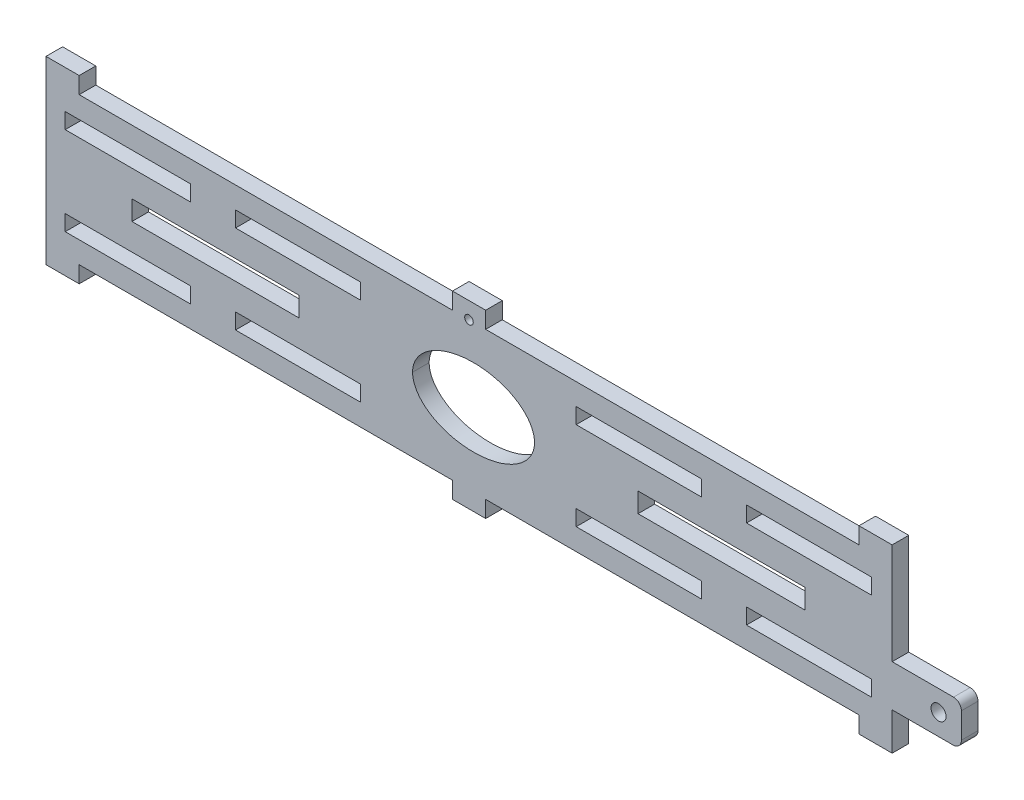
SolidWorks part; units mm, degrees
ref_plane "前视基准面" through (0, 0, 0) normal (0, 0, 1) x (1, 0, 0)
ref_plane "上视基准面" through (0, 0, 0) normal (0, 1, 0) x (1, 0, 0)
ref_plane "右视基准面" through (0, 0, 0) normal (1, 0, 0) x (0, 0, -1)
sketch "草图1" plane through (0, 0, 0) normal (0, 0, 1) x (1, 0, 0)
  line L0 (17.1779, 1.1844) -> (17.1779, -1.1844)
  line L1 (37.2925, 1.1844) -> (17.1779, 1.1844)
  line L2 (37.2925, -1.1844) -> (37.2925, 1.1844)
  line L3 (17.1779, -1.1844) -> (37.2925, -1.1844)
  line L4 (45.3383, -4.3798) -> (30.2524, -4.3798)
  line L5 (45.3383, -6.2719) -> (45.3383, -4.3798)
  line L6 (30.2524, -6.2719) -> (45.3383, -6.2719)
  line L7 (30.2524, -4.3798) -> (30.2524, -6.2719)
  line L8 (-50.1906, 8.875) -> (-50.1906, 10.875)
  line L9 (-50.1906, 10.875) -> (-54.1906, 10.875)
  line L10 (-54.1906, 10.875) -> (-54.1906, -10.875)
  line L11 (-1.1906, 10.875) -> (-5.1906, 10.875)
  line L12 (-50.1906, -10.875) -> (-50.1906, -8.875)
  line L13 (-50.1906, -8.875) -> (-5.1906, -8.875)
  line L14 (-5.1906, -8.875) -> (-5.1906, -10.875)
  line L15 (-1.1906, -10.875) -> (-5.1906, -10.875)
  line L16 (-1.1906, -10.875) -> (-1.1906, -8.875)
  line L17 (-1.1906, -8.875) -> (43.8094, -8.875)
  line L18 (43.8094, -8.875) -> (43.8094, -10.875)
  line L19 (-50.1906, -10.875) -> (-54.1906, -10.875)
  line L20 (47.8094, -10.875) -> (47.8094, -6.3479)
  line L21 (47.8094, -6.3479) -> (55.152, -6.3479)
  line L22 (56.1578, -5.3421) -> (56.1578, -2.2702)
  line L23 (55.2068, -1.3192) -> (47.8094, -1.3192)
  line L24 (47.8094, -1.3192) -> (47.8094, 10.875)
  line L25 (-43.8297, 0) -> (37.2925, 0) construction
  line L26 (43.8094, 10.875) -> (43.8094, 8.875)
  line L27 (43.8094, 8.875) -> (-1.1906, 8.875)
  line L28 (-1.1906, 8.875) -> (-1.1906, 10.875)
  line L29 (-43.8297, 0) -> (-54.1906, 0) construction
  line L30 (-5.1906, 10.875) -> (-5.1906, 8.875)
  line L31 (-5.1906, 8.875) -> (-50.1906, 8.875)
  line L32 (24.8063, -4.3798) -> (9.7204, -4.3798)
  line L33 (24.8063, -6.2719) -> (24.8063, -4.3798)
  line L34 (9.7204, -6.2719) -> (24.8063, -6.2719)
  line L35 (9.7204, -4.3798) -> (9.7204, -6.2719)
  line L36 (-16.2576, -4.3798) -> (-31.3436, -4.3798)
  line L37 (-16.2576, -6.2719) -> (-16.2576, -4.3798)
  line L38 (-31.3436, -6.2719) -> (-16.2576, -6.2719)
  line L39 (-31.3436, -4.3798) -> (-31.3436, -6.2719)
  line L40 (-36.7896, -4.3798) -> (-51.8755, -4.3798)
  line L41 (-36.7896, -6.2719) -> (-36.7896, -4.3798)
  line L42 (-51.8755, -6.2719) -> (-36.7896, -6.2719)
  line L43 (-51.8755, -4.3798) -> (-51.8755, -6.2719)
  line L44 (-43.8297, -1.1844) -> (-23.7151, -1.1844)
  line L45 (-43.8297, 1.1844) -> (-43.8297, -1.1844)
  line L46 (-23.7151, 1.1844) -> (-43.8297, 1.1844)
  line L47 (-23.7151, -1.1844) -> (-23.7151, 1.1844)
  line L48 (30.2524, 6.2719) -> (30.2524, 4.3798)
  line L49 (45.3383, 6.2719) -> (30.2524, 6.2719)
  line L50 (45.3383, 4.3798) -> (45.3383, 6.2719)
  line L51 (30.2524, 4.3798) -> (45.3383, 4.3798)
  line L52 (9.7204, 6.2719) -> (9.7204, 4.3798)
  line L53 (24.8063, 6.2719) -> (9.7204, 6.2719)
  line L54 (24.8063, 4.3798) -> (24.8063, 6.2719)
  line L55 (9.7204, 4.3798) -> (24.8063, 4.3798)
  line L56 (-31.3436, 6.2719) -> (-31.3436, 4.3798)
  line L57 (-16.2576, 6.2719) -> (-31.3436, 6.2719)
  line L58 (-16.2576, 4.3798) -> (-16.2576, 6.2719)
  line L59 (-31.3436, 4.3798) -> (-16.2576, 4.3798)
  line L60 (-51.8755, 6.2719) -> (-51.8755, 4.3798)
  line L61 (-36.7896, 6.2719) -> (-51.8755, 6.2719)
  line L62 (-36.7896, 4.3798) -> (-36.7896, 6.2719)
  line L63 (-51.8755, 4.3798) -> (-36.7896, 4.3798)
  line L65 (47.8094, -10.875) -> (43.8094, -10.875)
  line L67 (47.8094, 10.875) -> (43.8094, 10.875)
  circle A0 centre (-3.2018, 8.8716) radius 0.5151
  circle A1 centre (53.399, -3.8062) radius 0.9052
  arc A6 (55.152, -6.3479) -> (56.1578, -5.3421) centre (55.152, -5.3421) ccw
  arc A7 (56.1578, -2.2702) -> (55.2068, -1.3192) centre (55.2068, -2.2702) ccw
  spline S0 degree 3 poles (-10.0016, 0) (-10.0016, -9.3535) (4.6969, -9.3535) (4.6969, 0) knots 0 0 0 0 1 1 1 1 weights 1 0.333333 0.333333 1
  spline S1 degree 3 poles (4.6969, 0) (4.6969, 9.3535) (-10.0016, 9.3535) (-10.0016, 0) knots 0 0 0 0 1 1 1 1 weights 1 0.333333 0.333333 1
  point P6 (56.1578, -3.8062)
  point P91 (0, 0)
  dimension "D1" = 45
  dimension "D2" = 4
  dimension "D3" = 45
  dimension "D4" = 4
  dimension "D5" = 21.75
  dimension "D6" = 2
  dimension "D7" = 2
  dimension "D8" = 4
extrude "凸台-拉伸1" add sketch "草图1" along normal blind 2
